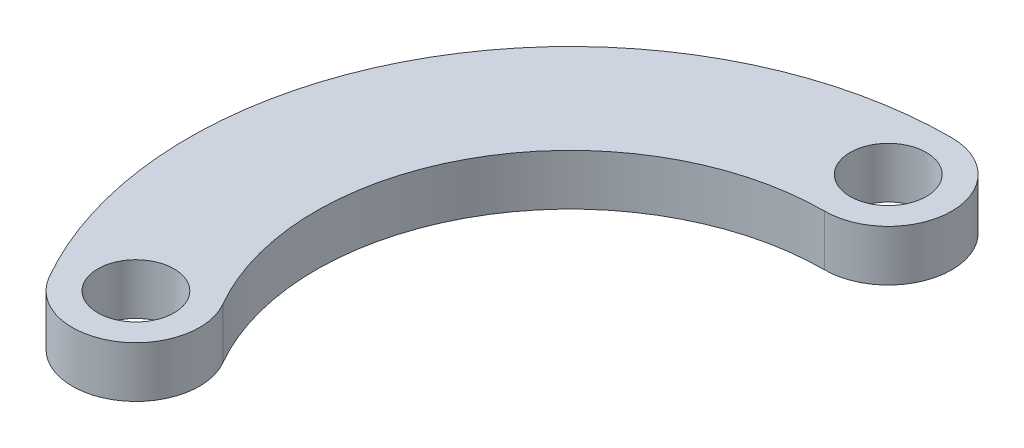
SolidWorks part; units mm, degrees
ref_plane "Front Plane" through (0, 0, 0) normal (0, 0, 1) x (1, 0, 0)
ref_plane "Top Plane" through (0, 0, 0) normal (0, 1, 0) x (1, 0, 0)
ref_plane "Right Plane" through (0, 0, 0) normal (1, 0, 0) x (0, 0, -1)
sketch "Sketch2" plane through (0, 0, 0) normal (0, 1, 0) x (1, 0, 0)
  circle A0 centre (0, 0) radius 10
  circle A1 centre (0, 0) radius 15
  circle A2 centre (0, 12.5) radius 1.5
  circle A3 centre (10.8253, -6.25) radius 1.5
  circle A4 centre (-10.8253, -6.25) radius 1.5
  point P13 (0, 0)
  dimension "D1" = 20
  dimension "D2" = 30
  dimension "D3" = 3
  dimension "D4" = 12.5
  dimension "D5" = 3
extrude "Boss-Extrude3" add sketch "Sketch2" along normal blind 2
sketch "Sketch4" plane through (0, 2, 0) normal (0, 1, 0) x (1, 0, 0)
  line L0 (0, 0) -> (-10.8253, -6.25)
  line L1 (0, 15) -> (15, 15)
  line L2 (0, 15) -> (0, -17.2828)
  line L3 (0, -17.2828) -> (15, -17.2828)
  line L4 (15, 15) -> (15, -17.2828)
  line L5 (0, 0) -> (9.1897, -15.9171)
  line L6 (-10.8253, -6.25) -> (-1.6356, -22.1671)
  line L7 (9.1897, -15.9171) -> (-1.6356, -22.1671)
  line L8 (-10.8253, -6.25) -> (-12.9904, -7.5)
  line L9 (-10.8253, -6.25) -> (-3.248, -19.3744)
  line L10 (-12.9904, -7.5) -> (-5.413, -20.6244)
  line L11 (-3.248, -19.3744) -> (-5.413, -20.6244)
  circle A0 centre (0, 0) radius 15 construction
  circle M5 centre (10.8253, -6.25) radius 1.5
  circle M6 centre (0, 0) radius 10
  circle M7 centre (0, 0) radius 15
  circle M8 centre (0, 12.5) radius 1.5
  circle M9 centre (-10.8253, -6.25) radius 1.5
extrude "Cut-Extrude1" cut sketch "Sketch4" against normal blind 2 contours L5 L7 L2 M7 M8 M6 M5 | L8 L6 M9 M7 | L7 L2 L0 L6 M6 M9 M7 | L7 L5 L2 M6
sketch "Sketch5" plane through (0, 2, 0) normal (0, 1, 0) x (1, 0, 0)
  circle A0 centre (0, 12.5) radius 2.5
  circle A1 centre (0, 12.5) radius 1.5
  circle A2 centre (-10.8253, -6.25) radius 2.5
  circle A3 centre (-10.8253, -6.25) radius 1.5
  dimension "D1" = 5
  dimension "D2" = 3
  dimension "D3" = 5
  dimension "D4" = 3
extrude "Boss-Extrude4" add sketch "Sketch5" against normal blind 2
